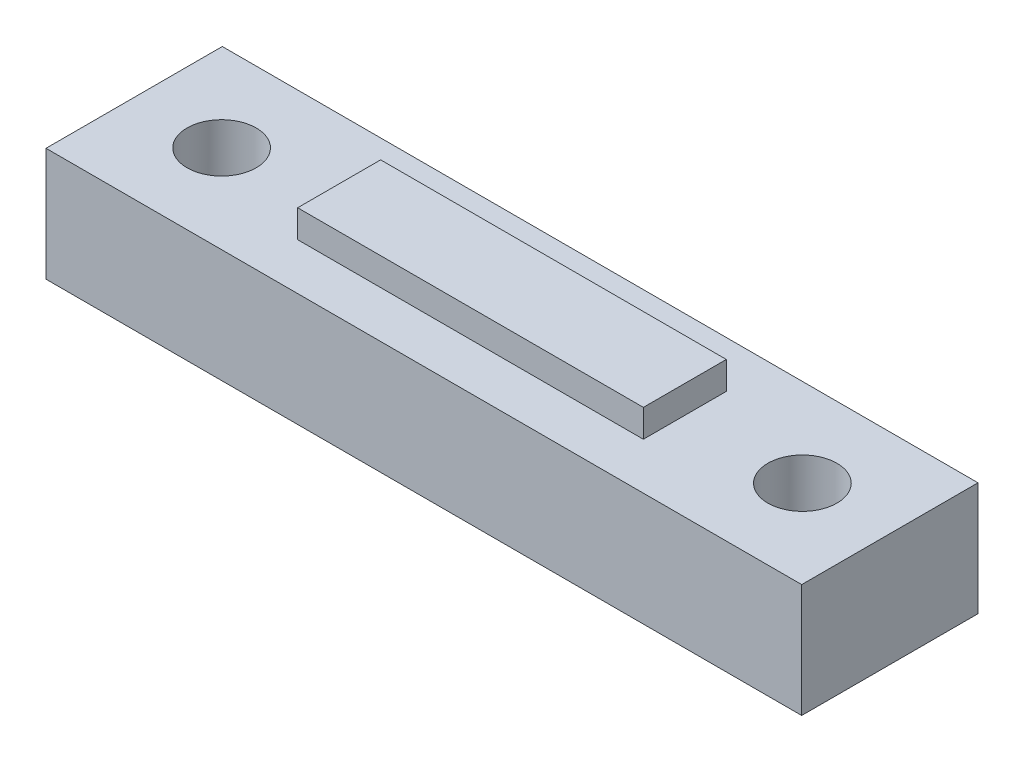
SolidWorks part; units mm, degrees
ref_plane "Front Plane" through (0, 0, 0) normal (0, 0, 1) x (1, 0, 0)
ref_plane "Top Plane" through (0, 0, 0) normal (0, 1, 0) x (1, 0, 0)
ref_plane "Right Plane" through (0, 0, 0) normal (1, 0, 0) x (0, 0, -1)
sketch "Sketch1" plane through (0, 0, 0) normal (0, 1, 0) x (1, 0, 0)
  line L1 (0, 0) -> (54.65, 0)
  line L2 (0, 0) -> (0, 12.75)
  line L3 (0, 12.75) -> (54.65, 12.75)
  line L4 (54.65, 0) -> (54.65, 12.75)
  dimension "D1" = 12.75
  dimension "D2" = 54.65
extrude "Boss-Extrude1" add sketch "Sketch1" along normal blind 8.2
sketch "Sketch2" plane through (0, 8.2, 0) normal (0, 1, 0) x (1, 0, 0)
  line L1 (54.65, 12.75) -> (0, 12.75) construction
  circle A0 centre (6.325, 6.375) radius 2.5
  circle A1 centre (48.325, 6.375) radius 2.5
  dimension "D1" = 42
  dimension "D2" = 6.375
extrude "Cut-Extrude2" cut sketch "Sketch2" against normal blind 10
sketch "Sketch3" plane through (0, 8.2, 0) normal (0, 1, 0) x (1, 0, 0)
  line L0 (0, 12.75) -> (0, 0) construction
  line L1 (39.825, 3.375) -> (14.825, 3.375)
  line L2 (39.825, 3.375) -> (39.825, 9.375)
  line L3 (39.825, 9.375) -> (14.825, 9.375)
  line L4 (14.825, 3.375) -> (14.825, 9.375)
  dimension "D1" = 6
  dimension "D2" = 14.825
  dimension "D3" = 25
extrude "Boss-Extrude2" add sketch "Sketch3" along normal blind 2
